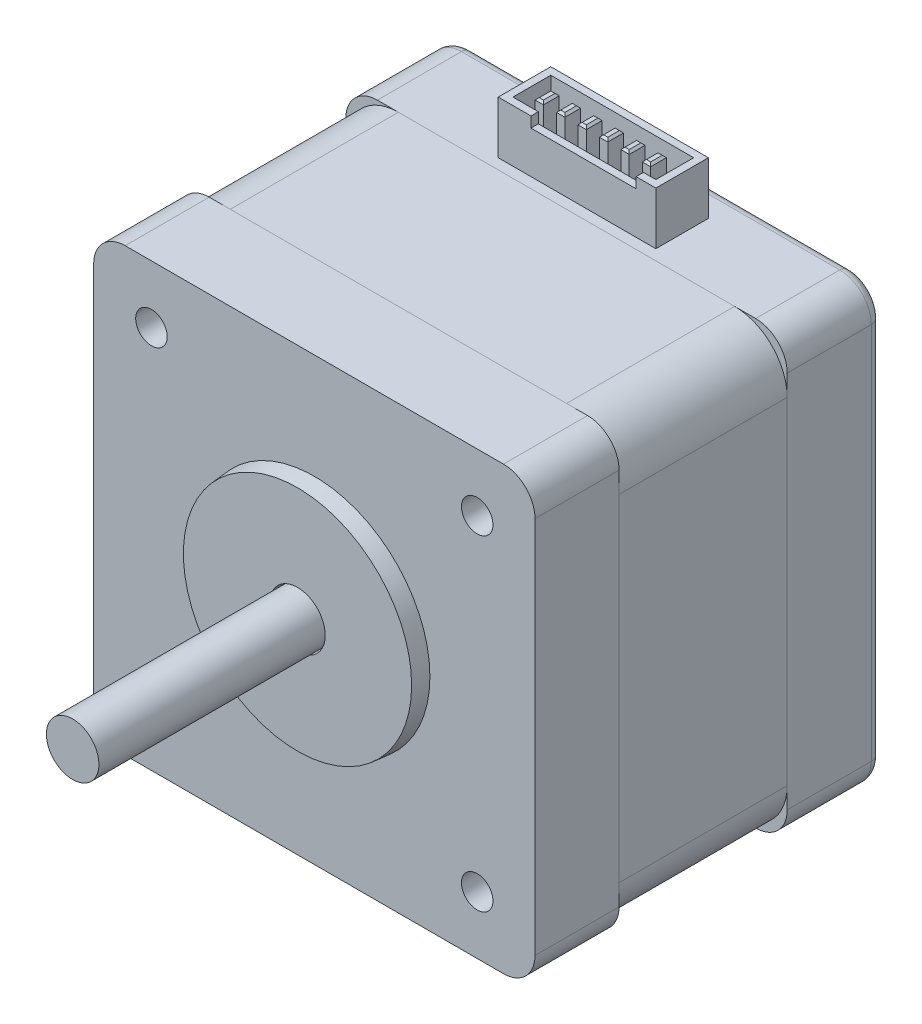
SolidWorks part; units mm, degrees
material "氧化铝"
ref_plane "前视基准面" through (0, 0, 0) normal (0, 0, 1) x (1, 0, 0)
ref_plane "上视基准面" through (0, 0, 0) normal (0, 1, 0) x (1, 0, 0)
ref_plane "右视基准面" through (0, 0, 0) normal (1, 0, 0) x (0, 0, -1)
sketch "草图1" plane through (0, 0, 0) normal (0, 0, 1) x (1, 0, 0)
  line L0 (0, 21) -> (0, -21) construction
  line L1 (-18, 21) -> (18, 21)
  line L2 (-21, 18) -> (-21, -18)
  line L3 (-18, -21) -> (18, -21)
  line L4 (21, 18) -> (21, -18)
  line L5 (-21, 21) -> (21, -21) construction
  line L6 (-21, -21) -> (21, 21) construction
  line L7 (-15.5, 15.5) -> (15.5, 15.5) construction
  line L8 (-15.5, 15.5) -> (-15.5, -15.5) construction
  line L9 (-15.5, -15.5) -> (15.5, -15.5) construction
  line L10 (15.5, 15.5) -> (15.5, -15.5) construction
  line L11 (-15.5, 15.5) -> (15.5, -15.5) construction
  line L12 (-15.5, -15.5) -> (15.5, 15.5) construction
  line L13 (-21, 0) -> (21, 0) construction
  circle A0 centre (-15.5, 15.5) radius 1.5
  circle A1 centre (15.5, 15.5) radius 1.5
  circle A2 centre (15.5, -15.5) radius 1.5
  circle A3 centre (-15.5, -15.5) radius 1.5
  arc A4 (-18, -21) -> (-21, -18) centre (-18, -18) cw
  arc A5 (18, -21) -> (21, -18) centre (18, -18) ccw
  arc A6 (21, 18) -> (18, 21) centre (18, 18) ccw
  arc A7 (-21, 18) -> (-18, 21) centre (-18, 18) cw
  point P0 (0, 0)
  point P6 (0, 0)
  dimension "D4" = 3
  dimension "D5" = 3
  dimension "D1" = 42
  dimension "D2" = 42
  dimension "D3" = 31
extrude "凸台-拉伸1" add sketch "草图1" along normal blind 8
sketch "草图4" plane through (0, 0, 8) normal (0, 0, 1) x (1, 0, 0)
  circle A0 centre (0, 0) radius 2.5
  dimension "D1" = 5
extrude "凸台-拉伸2" add sketch "草图4" along normal blind 23
sketch "草图9" plane through (0, 0, 0) normal (0, 0, -1) x (-1, 0, 0)
  line L1 (-21, 21) -> (21, 21)
  line L2 (-21, 21) -> (-21, -21)
  line L3 (-21, -21) -> (21, -21)
  line L4 (21, 21) -> (21, -21)
  line L5 (-21, 21) -> (21, -21) construction
  line L6 (-21, -21) -> (21, 21) construction
  point P0 (0, 0)
  dimension "D1" = 42
  dimension "D2" = 42
extrude "凸台-拉伸7" add sketch "草图9" along normal blind 16 separate body
sketch "草图10" plane through (0, 0, -16) normal (0, 0, -1) x (-1, 0, 0)
  line L1 (-21, 21) -> (21, 21)
  line L2 (-21, 21) -> (-21, -21)
  line L3 (-21, -21) -> (21, -21)
  line L4 (21, 21) -> (21, -21)
extrude "凸台-拉伸8" add sketch "草图10" along normal blind 9 separate body
fillet "圆角1" radius 3 4 edges at (21, -21, -20.5) (-21, -21, -20.5) (-21, 21, -20.5) (21, 21, -20.5)
fillet "圆角2" radius 5 4 edges at (-21, -21, -8) (-21, 21, -8) (21, 21, -8) (21, -21, -8)
sketch "草图13" plane through (0, 0, -25) normal (0, 0, -1) x (-1, 0, 0)
  circle A0 centre (0, 0) radius 2.5
extrude "凸台-拉伸9" [suppressed] add sketch "草图13" along normal blind 12
sketch "草图14" plane through (0, 21, 0) normal (0, 1, 0) x (1, 0, 0)
  line L0 (-18, 25) -> (18, 25) construction
  line L1 (-7.5, 22) -> (7.5, 22)
  line L2 (-7.5, 22) -> (-7.5, 17)
  line L3 (-7.5, 17) -> (7.5, 17)
  line L4 (7.5, 22) -> (7.5, 17)
  line L5 (-6.8, 21.3) -> (6.8, 21.3)
  line L6 (6.8, 21.3) -> (6.8, 17.7)
  line L7 (-6.8, 17.7) -> (6.8, 17.7)
  line L8 (-6.8, 21.3) -> (-6.8, 17.7)
  line L9 (-3.66, 20.2073) -> (-2.86, 20.2073)
  line L10 (-5.7, 20.2073) -> (-4.9, 20.2073)
  line L11 (-5.7, 20.2073) -> (-5.7, 18.7073)
  line L12 (-5.7, 18.7073) -> (-4.9, 18.7073)
  line L13 (-4.9, 20.2073) -> (-4.9, 18.7073)
  line L14 (-5.7, 20.2073) -> (-4.9, 18.7073) construction
  line L15 (-5.7, 18.7073) -> (-4.9, 20.2073) construction
  line L16 (-3.66, 20.2073) -> (-3.66, 18.7073)
  line L17 (-3.66, 18.7073) -> (-2.86, 18.7073)
  line L18 (-2.86, 20.2073) -> (-2.86, 18.7073)
  line L19 (-3.66, 20.2073) -> (-2.86, 18.7073) construction
  line L20 (-3.66, 18.7073) -> (-2.86, 20.2073) construction
  line L21 (-1.62, 20.2073) -> (-0.82, 20.2073)
  line L22 (-1.62, 20.2073) -> (-1.62, 18.7073)
  line L23 (-1.62, 18.7073) -> (-0.82, 18.7073)
  line L24 (-0.82, 20.2073) -> (-0.82, 18.7073)
  line L25 (-1.62, 20.2073) -> (-0.82, 18.7073) construction
  line L26 (-1.62, 18.7073) -> (-0.82, 20.2073) construction
  line L27 (0.42, 20.2073) -> (1.22, 20.2073)
  line L28 (0.42, 20.2073) -> (0.42, 18.7073)
  line L29 (0.42, 18.7073) -> (1.22, 18.7073)
  line L30 (1.22, 20.2073) -> (1.22, 18.7073)
  line L31 (0.42, 20.2073) -> (1.22, 18.7073) construction
  line L32 (0.42, 18.7073) -> (1.22, 20.2073) construction
  line L33 (2.46, 20.2073) -> (3.26, 20.2073)
  line L34 (2.46, 20.2073) -> (2.46, 18.7073)
  line L35 (2.46, 18.7073) -> (3.26, 18.7073)
  line L36 (3.26, 20.2073) -> (3.26, 18.7073)
  line L37 (2.46, 20.2073) -> (3.26, 18.7073) construction
  line L38 (2.46, 18.7073) -> (3.26, 20.2073) construction
  line L39 (4.5, 20.2073) -> (5.3, 20.2073)
  line L40 (4.5, 20.2073) -> (4.5, 18.7073)
  line L41 (4.5, 18.7073) -> (5.3, 18.7073)
  line L42 (5.3, 20.2073) -> (5.3, 18.7073)
  line L43 (4.5, 20.2073) -> (5.3, 18.7073) construction
  line L44 (4.5, 18.7073) -> (5.3, 20.2073) construction
  line L45 (0, 25) -> (0, 22) construction
  point P11 (-5.3, 19.4573)
  point P18 (-3.26, 19.4573)
  point P23 (-1.22, 19.4573)
  point P28 (0.82, 19.4573)
  point P33 (2.86, 19.4573)
  point P38 (4.9, 19.4573)
  dimension "D1" = 15
  dimension "D2" = 5
  dimension "D3" = 3
  dimension "D4" = 0.7
  dimension "D5" = 1.5
  dimension "D6" = 0.8
  dimension "D8" = 1.5
  dimension "D9" = 1.5
  dimension "D7" = 6
extrude "凸台-拉伸10" add sketch "草图14" along normal blind 5 contours L4 L1 L2 L3 L8 L5 L6 L7 | L13 L10 L11 L12 | L24 L21 L22 L23 | L42 L39 L40 L41 | L36 L33 L34 L35 | L9 L18 L17 L16 | L27 L30 L29 L28
chamfer "倒角1" distance 0.2 angle 45 24 edges at (4.9, 26, -18.7073) (4.5, 26, -19.4573) (4.9, 26, -20.2073) (5.3, 26, -19.4573) (2.86, 26, -18.7073) (2.46, 26, -19.4573) (2.86, 26, -20.2073) (3.26, 26, -19.4573) (0.82, 26, -20.2073) (1.22, 26, -19.4573) (0.82, 26, -18.7073) (0.42, 26, -19.4573) (-1.22, 26, -18.7073) (-1.62, 26, -19.4573) (-1.22, 26, -20.2073) (-0.82, 26, -19.4573) (-3.26, 26, -20.2073) (-2.86, 26, -19.4573) (-3.26, 26, -18.7073) (-3.66, 26, -19.4573) (-5.3, 26, -18.7073) (-5.7, 26, -19.4573) (-5.3, 26, -20.2073) (-4.9, 26, -19.4573)
sketch "草图15" plane through (0, 0, -17) normal (0, 0, 1) x (1, 0, 0)
  line L0 (0.62, 26) -> (0.62, 22.2151) construction
  line L1 (-4.38, 26) -> (-4.38, 25)
  line L2 (-7.5, 26) -> (7.5, 26) construction
  line L3 (-4.38, 25) -> (5.62, 25)
  line L4 (5.62, 26) -> (5.62, 25)
  line L5 (-4.38, 26) -> (5.62, 26)
  point P9 (0.62, 25)
  dimension "D1" = 5
  dimension "D2" = 1
extrude "切除-拉伸2" cut sketch "草图15" against normal up to next (0.7 mm away)
fillet "圆角3" radius 1 8 edges at (20.1213, 20.1213, -25) (-20.1213, 20.1213, -25) (-21, 0, -25) (-20.1213, -20.1213, -25) (0, -21, -25) (20.1213, -20.1213, -25) (21, 0, -25) (0, 21, -25)
sketch "草图16" plane through (0, 0, 8) normal (0, 0, 1) x (1, 0, 0)
  circle A0 centre (0, 0) radius 11
  circle A1 centre (0, 0) radius 2.5 construction
  circle A2 centre (0, 0) radius 2.5
  dimension "D1" = 22
extrude "凸台-拉伸11" add sketch "草图16" along normal blind 1.6 draft 5
sketch "草图17" [suppressed] plane through (0, 0, -39) normal (0, 0, -1) x (-1, 0, 0)
  circle A0 centre (0, 0) radius 2.5
  dimension "D1" = 5
extrude "凸台-拉伸12" [suppressed] add sketch "草图17" along normal blind 15
